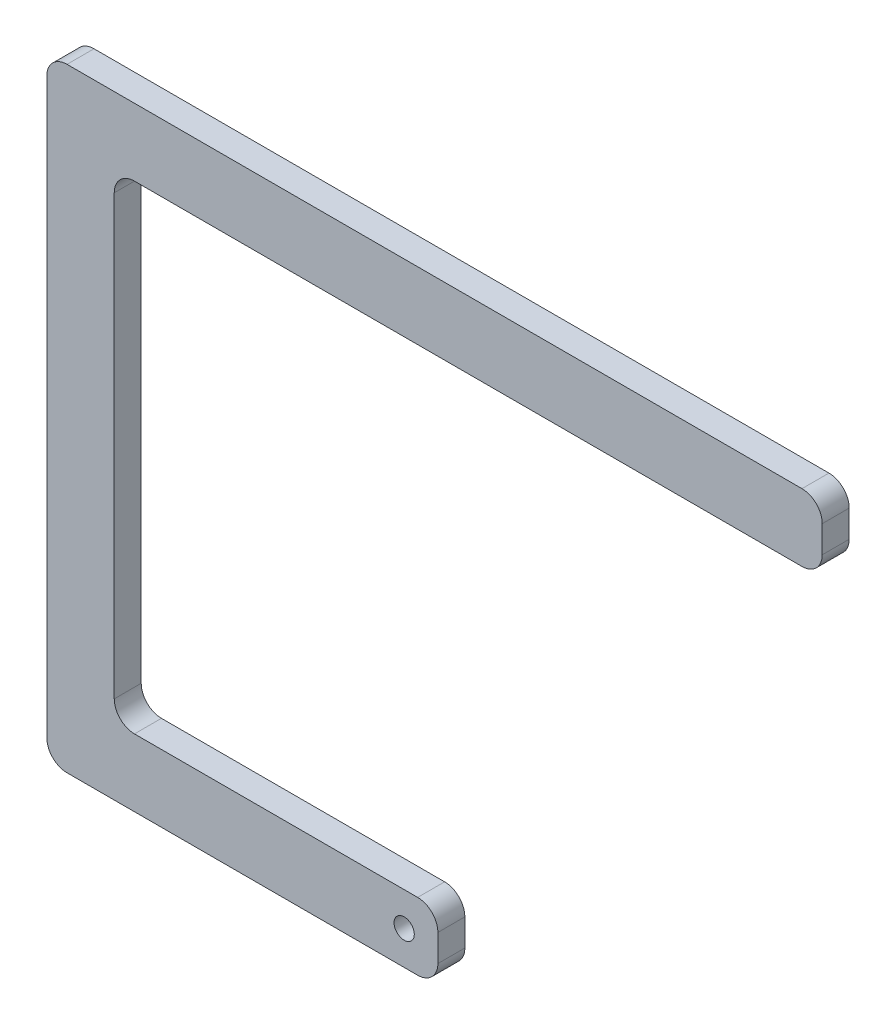
SolidWorks part; units mm, degrees
ref_plane "Front Plane" through (0, 0, 0) normal (0, 0, 1) x (1, 0, 0)
ref_plane "Top Plane" through (0, 0, 0) normal (0, 1, 0) x (1, 0, 0)
ref_plane "Right Plane" through (0, 0, 0) normal (1, 0, 0) x (0, 0, -1)
sketch "Sketch1" plane through (0, 0, 0) normal (0, 0, 1) x (1, 0, 0)
  line L0 (-3, 0) -> (-45, 0)
  line L1 (-48, 3) -> (-48, 68)
  line L2 (-45, 71) -> (54, 71)
  line L3 (-3, -10) -> (-55, -10)
  line L4 (-58, -7) -> (-58, 78)
  line L5 (-55, 81) -> (54, 81)
  line L6 (0, -3) -> (0, -7)
  line L7 (57, 74) -> (57, 78)
  line L8 (-58, -10) -> (-58, 81) construction
  line L9 (-58, 81) -> (50, 81) construction
  line L10 (0, -10) -> (-58, -10) construction
  line L11 (-48, 71) -> (50, 71) construction
  line L12 (-48, 0) -> (-48, 71) construction
  line L13 (0, 0) -> (-48, 0) construction
  arc A0 (-58, 78) -> (-55, 81) centre (-55, 78) cw
  arc A1 (-55, -10) -> (-58, -7) centre (-55, -7) cw
  arc A2 (54, 71) -> (57, 74) centre (54, 74) ccw
  arc A3 (-48, 68) -> (-45, 71) centre (-45, 68) cw
  arc A4 (-45, 0) -> (-48, 3) centre (-45, 3) cw
  arc A5 (-3, 0) -> (0, -3) centre (-3, -3) cw
  arc A6 (-3, -10) -> (0, -7) centre (-3, -7) ccw
  arc A7 (54, 81) -> (57, 78) centre (54, 78) cw
  circle A8 centre (-5, -5) radius 1.5
  point P18 (57, 71)
  dimension "D5" = 3
  dimension "D6" = 3
  dimension "D7" = 3
  dimension "D8" = 5
  dimension "D9" = 5
  dimension "D1" = 91
  dimension "D2" = 58
  dimension "D3" = 115
  dimension "D4" = 10
extrude "Boss-Extrude1" add sketch "Sketch1" along normal blind 4
